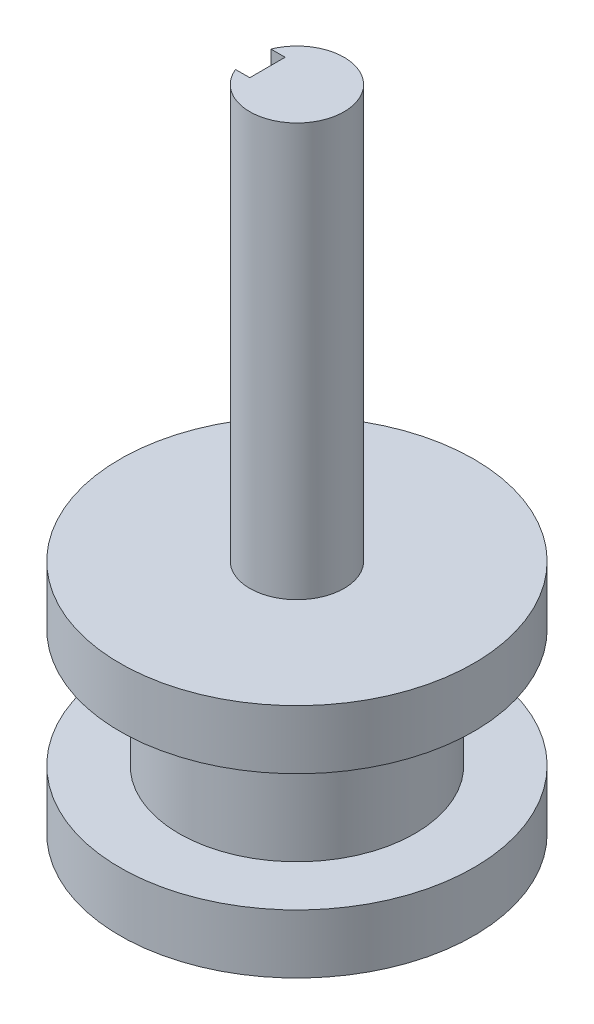
SolidWorks part; units mm, degrees
ref_plane "Front Plane" through (0, 0, 0) normal (0, 0, 1) x (1, 0, 0)
ref_plane "Top Plane" through (0, 0, 0) normal (0, 1, 0) x (1, 0, 0)
ref_plane "Right Plane" through (0, 0, 0) normal (1, 0, 0) x (0, 0, -1)
sketch "Sketch1" plane through (0, 0, 0) normal (0, 1, 0) x (1, 0, 0)
  circle A0 centre (0, 0) radius 4
  dimension "D1" = 8
extrude "Boss-Extrude1" add sketch "Sketch1" along normal blind 35
sketch "Sketch4" plane through (0, 35, 0) normal (0, 1, 0) x (1, 0, 0)
  line L1 (-5.5, 1.5) -> (-2.5, 1.5)
  line L2 (-5.5, 1.5) -> (-5.5, -1.5)
  line L3 (-5.5, -1.5) -> (-2.5, -1.5)
  line L4 (-2.5, 1.5) -> (-2.5, -1.5)
  line L5 (-5.5, 1.5) -> (-2.5, -1.5) construction
  line L6 (-5.5, -1.5) -> (-2.5, 1.5) construction
  circle A0 centre (0, 0) radius 4 construction
  point P3 (-4, 0)
  dimension "D2" = 8
  dimension "D1" = 3
extrude "Cut-Extrude3" cut sketch "Sketch4" against normal blind 5
sketch "Sketch5" plane through (0, 0, 0) normal (0, -1, 0) x (1, 0, 0)
  circle A0 centre (0, 0) radius 15
  dimension "D1" = 30
extrude "Boss-Extrude2" add sketch "Sketch5" along normal blind 5
sketch "Sketch6" plane through (0, -5, 0) normal (0, -1, 0) x (1, 0, 0)
  circle A0 centre (0, 0) radius 10
  dimension "D1" = 20
extrude "Boss-Extrude3" add sketch "Sketch6" along normal blind 10
sketch "Sketch7" plane through (0, -15, 0) normal (0, -1, 0) x (1, 0, 0)
  circle A0 centre (0, 0) radius 15
extrude "Boss-Extrude4" add sketch "Sketch7" along normal blind 5
